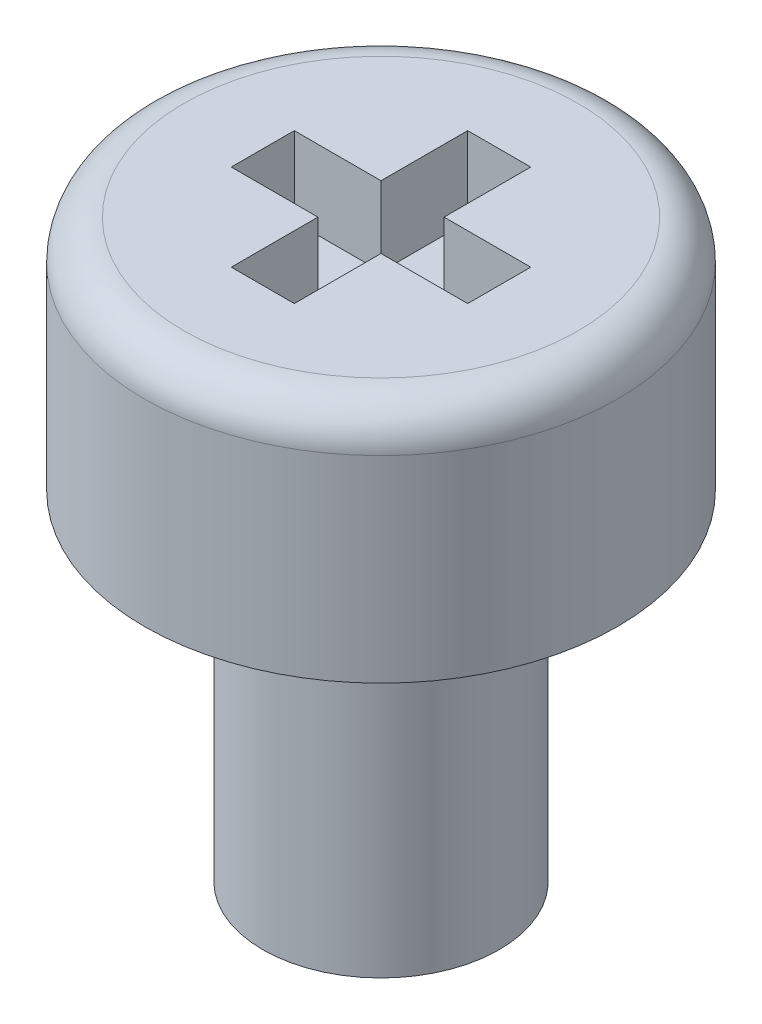
SolidWorks part; units mm, degrees
ref_plane "Front Plane" through (0, 0, 0) normal (0, 0, 1) x (1, 0, 0)
ref_plane "Top Plane" through (0, 0, 0) normal (0, 1, 0) x (1, 0, 0)
ref_plane "Right Plane" through (0, 0, 0) normal (1, 0, 0) x (0, 0, -1)
sketch "Sketch1" plane through (0, 0, 0) normal (0, 1, 0) x (1, 0, 0)
  circle A0 centre (0, 0) radius 3
  dimension "D1" = 6
extrude "Boss-Extrude1" add sketch "Sketch1" along normal blind 3
sketch "Sketch2" plane through (0, 0, 0) normal (0, -1, 0) x (1, 0, 0)
  circle A0 centre (0, 0) radius 1.5
  dimension "D1" = 3
extrude "Boss-Extrude2" add sketch "Sketch2" along normal blind 4.3
fillet "Fillet1" radius 0.5 1 edges at (0, 3, 3)
sketch "Sketch3" plane through (0, 3, 0) normal (0, 1, 0) x (1, 0, 0)
  line L1 (0.4, 1.5) -> (-0.4, 1.5)
  line L2 (0.4, 1.5) -> (0.4, -1.5)
  line L3 (0.4, -1.5) -> (-0.4, -1.5)
  line L4 (-0.4, 1.5) -> (-0.4, -1.5)
  line L5 (0.4, 1.5) -> (-0.4, -1.5) construction
  line L6 (0.4, -1.5) -> (-0.4, 1.5) construction
  line L7 (-1.5, 0.4) -> (1.5, 0.4)
  line L8 (-1.5, 0.4) -> (-1.5, -0.4)
  line L9 (-1.5, -0.4) -> (1.5, -0.4)
  line L10 (1.5, 0.4) -> (1.5, -0.4)
  line L11 (-1.5, 0.4) -> (1.5, -0.4) construction
  line L12 (-1.5, -0.4) -> (1.5, 0.4) construction
  point P0 (0, 0)
  point P6 (0, 0)
  dimension "D1" = 0.8
  dimension "D2" = 0.8
  dimension "D3" = 3
  dimension "D4" = 3
extrude "Cut-Extrude1" cut sketch "Sketch3" against normal blind 1 contours L4 L7 L2 L1 | L10 L7 L2 L9 | L9 L4 L3 L2 | L8 L9 L4 L7 | L4 L9 L2 L7
